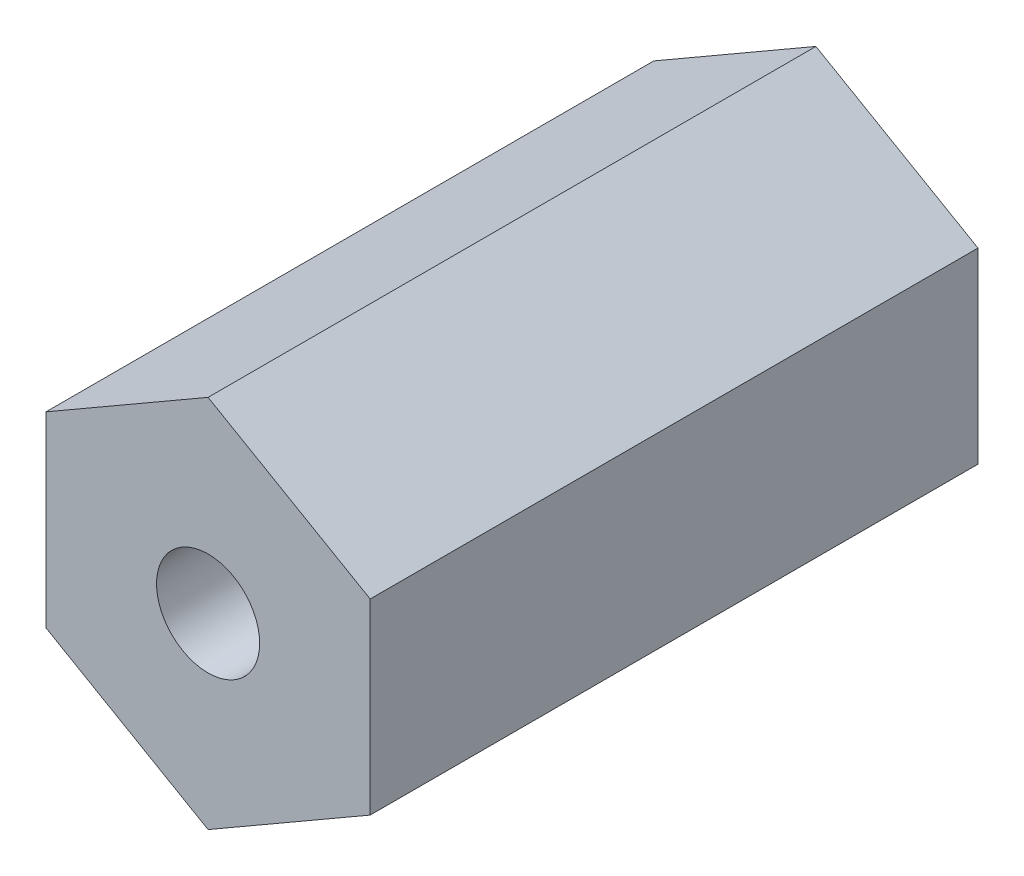
SolidWorks part; units mm, degrees
material "6061 Alloy"
ref_plane "Front Plane" through (0, 0, 0) normal (0, 0, 1) x (1, 0, 0)
ref_plane "Top Plane" through (0, 0, 0) normal (0, 1, 0) x (1, 0, 0)
ref_plane "Right Plane" through (0, 0, 0) normal (1, 0, 0) x (0, 0, -1)
sketch "Sketch1" plane through (0, 0, 0) normal (0, 0, 1) x (1, 0, 0)
  line L1 (0, 7.3323) -> (-6.35, 3.6662)
  line L2 (-6.35, 3.6662) -> (-6.35, -3.6662)
  line L3 (-6.35, -3.6662) -> (0, -7.3323)
  line L4 (0, -7.3323) -> (6.35, -3.6662)
  line L5 (6.35, -3.6662) -> (6.35, 3.6662)
  line L6 (6.35, 3.6662) -> (0, 7.3323)
  circle A0 centre (0, 0) radius 6.35 construction
  circle A1 centre (0, 0) radius 2.0193
  dimension "D1" = 12.7
  dimension "D2" = 4.0386
extrude "Boss-Extrude1" add sketch "Sketch1" along normal blind 23.8125
